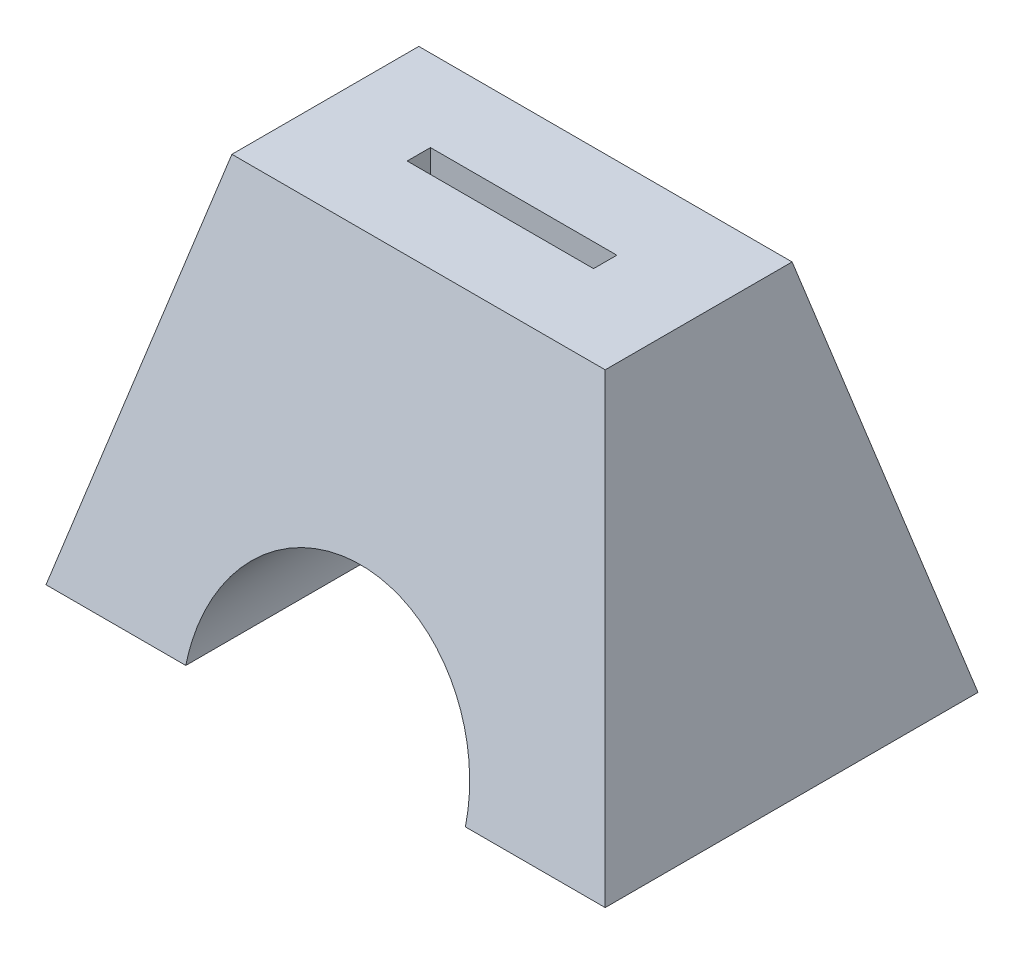
SolidWorks part; units mm, degrees
ref_plane "정면" through (0, 0, 0) normal (0, 0, 1) x (1, 0, 0)
ref_plane "윗면" through (0, 0, 0) normal (0, 1, 0) x (1, 0, 0)
ref_plane "우측면" through (0, 0, 0) normal (1, 0, 0) x (0, 0, -1)
sketch "스케치11" plane through (0, 0, 0) normal (0, 1, 0) x (1, 0, 0)
  line L1 (60, -40) -> (-60, -40)
  line L2 (60, -40) -> (60, 40)
  line L3 (60, 40) -> (-60, 40)
  line L4 (-60, -40) -> (-60, 40)
  line L5 (60, -40) -> (-60, 40) construction
  line L6 (60, 40) -> (-60, -40) construction
  point P0 (0, 0)
  dimension "D1" = 80
  dimension "D2" = 120
extrude "보스-돌출3" add sketch "스케치11" along normal blind 80 draft 14
sketch "스케치12" plane through (0, 0, 0) normal (0, 1, 0) x (1, 0, 0)
  line L1 (20, -2.5) -> (-20, -2.5)
  line L2 (20, -2.5) -> (20, 2.5)
  line L3 (20, 2.5) -> (-20, 2.5)
  line L4 (-20, -2.5) -> (-20, 2.5)
  line L5 (20, -2.5) -> (-20, 2.5) construction
  line L6 (20, 2.5) -> (-20, -2.5) construction
  point P0 (0, 0)
  dimension "D1" = 5
  dimension "D2" = 40
extrude "컷-돌출1" cut sketch "스케치12" against normal blind 20 from surface at 80 starting at face at (0, 80, 0)
sketch "스케치13" plane through (0, 0, 0) normal (0, 0, 1) x (1, 0, 0)
  circle A0 centre (0, 0) radius 30
  dimension "D1" = 60
extrude "컷-돌출2" cut sketch "스케치13" against normal through all and the other way through all
